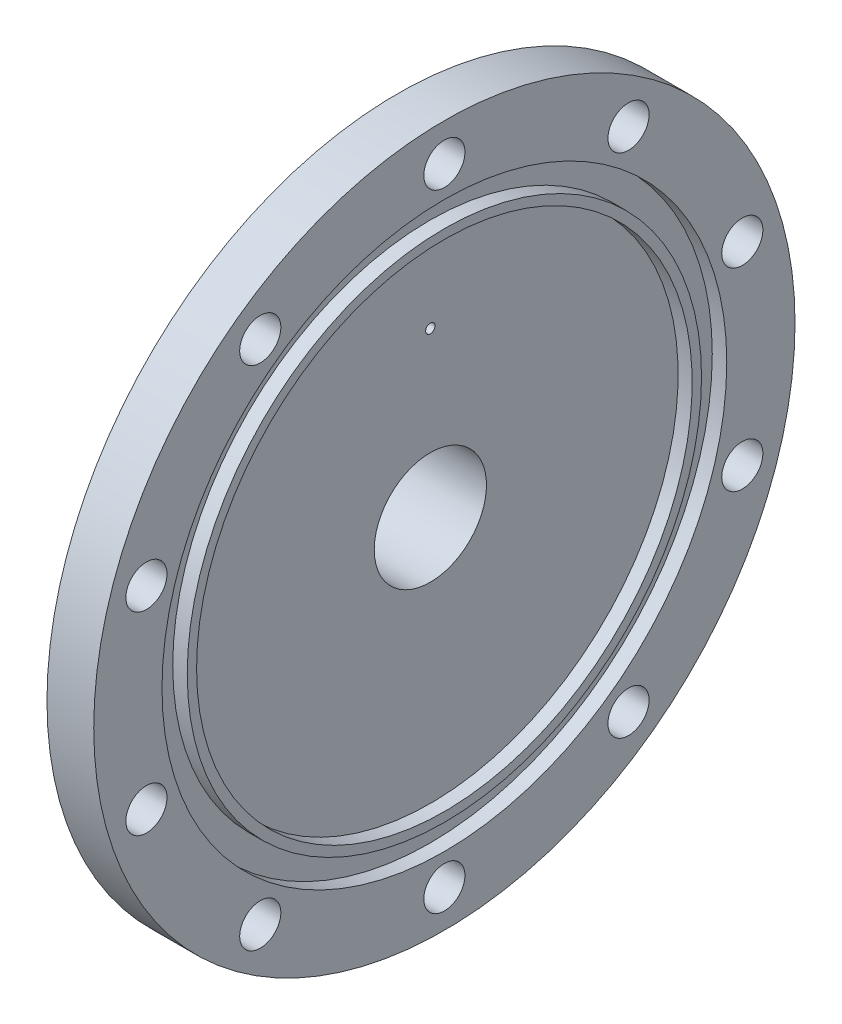
SolidWorks part; units mm, degrees
ref_plane "Front Plane" through (0, 0, 0) normal (0, 0, 1) x (1, 0, 0)
ref_plane "Top Plane" through (0, 0, 0) normal (0, 1, 0) x (1, 0, 0)
ref_plane "Right Plane" through (0, 0, 0) normal (1, 0, 0) x (0, 0, -1)
sketch "Sketch1" plane through (0, 0, 0) normal (0, 0, 1) x (1, 0, 0)
  line L0 (0, 0) -> (86.9024, 0) construction
  line L1 (0, 12) -> (17, 12)
  line L2 (0, 12) -> (0, 24)
  line L3 (0, 24) -> (10, 24)
  line L5 (10, 75) -> (20, 75)
  line L6 (10, 24) -> (10, 75)
  line L8 (20, 75) -> (20, 60.4)
  line L9 (20, 53) -> (17, 53)
  line L10 (17, 53) -> (17, 12)
  line L11 (20, 55) -> (16.9, 55)
  line L12 (16.9, 55) -> (16.9, 60.4)
  line L13 (16.9, 60.4) -> (20, 60.4)
  line L14 (20, 55) -> (20, 53)
  point P5 (20, 53.2)
  dimension "D2" = 2
  dimension "D3" = 12
  dimension "D4" = 12
  dimension "D5" = 3
  dimension "D6" = 75
  dimension "D7" = 10
  dimension "D8" = 3.1
  dimension "D9" = 5.4
  dimension "D10" = 20
  dimension "D11" = 17
  dimension "D12" = 53
  dimension "D13" = 0.2
revolve "Revolve1" add sketch "Sketch1" angle 360 about L0
sketch "Sketch2" plane through (0, 0, 0) normal (-1, 0, 0) x (0, 0, 1)
  circle A0 centre (0, 0) radius 18 construction
  circle A1 centre (0, 18) radius 2.1
extrude "Cut-Extrude1" cut sketch "Sketch2" against normal blind 6
pattern_circular "CirPattern1" count 6 over 360 about axis through (0, 0, 0) along (1, 0, 0) of "Cut-Extrude1"
sketch "Sketch3" plane through (10, 0, 0) normal (-1, 0, 0) x (0, 0, 1)
  circle A0 centre (0, 0) radius 67 construction
  circle A1 centre (0, 67) radius 4.4
extrude "Cut-Extrude2" cut sketch "Sketch3" against normal up to next
pattern_circular "CirPattern2" count 10 over 360 about axis through (0, 0, 0) along (1, 0, 0) of "Cut-Extrude2"
sketch "Sketch4" plane through (10, 0, 0) normal (-1, 0, 0) x (0, 0, 1)
  line L0 (-21.8435, 9.9429) -> (-8.6464, 38.9357)
  line L1 (0, 0) -> (0, 15.5415) construction
  line L2 (21.8435, 9.9429) -> (8.6464, 38.9357)
  circle A0 centre (0, 35) radius 5.5
  arc A1 (8.6464, 38.9357) -> (-8.6464, 38.9357) centre (0, 35) ccw
  arc A3 (21.8435, 9.9429) -> (-21.8435, 9.9429) centre (0, 0) ccw
  dimension "D1" = 35
extrude "Boss-Extrude1" add sketch "Sketch4" along normal blind 10
sketch "Sketch5" plane through (10, 0, 0) normal (-1, 0, 0) x (0, 0, 1)
  circle A0 centre (0, 35) radius 5.5
extrude "Cut-Extrude3" cut sketch "Sketch5" against normal blind 3
sketch "Sketch6" plane through (13, 0, 0) normal (-1, 0, 0) x (0, 0, 1)
  circle A0 centre (0, 35) radius 1
extrude "Cut-Extrude4" cut sketch "Sketch6" against normal up to next
